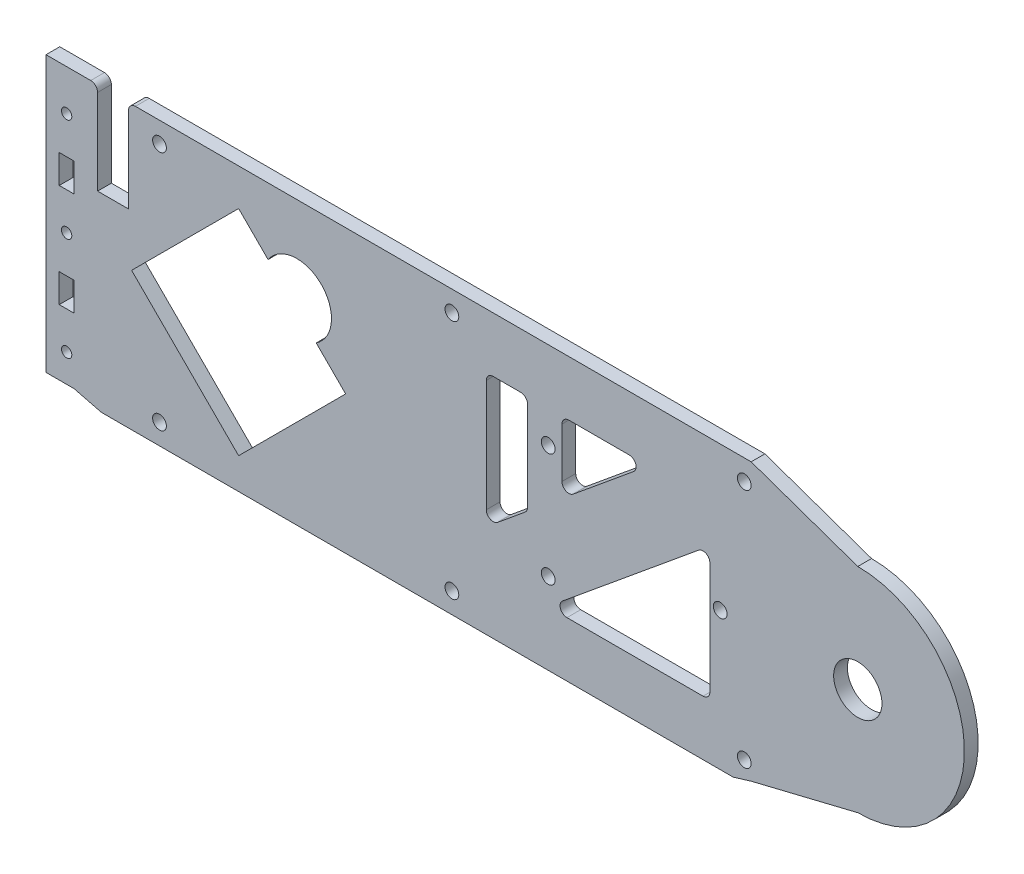
SolidWorks part; units mm, degrees
ref_plane "前视基准面" through (0, 0, 0) normal (0, 0, 1) x (1, 0, 0)
ref_plane "上视基准面" through (0, 0, 0) normal (0, 1, 0) x (1, 0, 0)
ref_plane "右视基准面" through (0, 0, 0) normal (1, 0, 0) x (0, 0, -1)
sketch "草图1" plane through (0, 0, 0) normal (0, 0, 1) x (1, 0, 0)
  line L0 (0.5429, 31.3543) -> (0.5429, 28.3543)
  line L1 (0.5429, 18.8543) -> (0.5429, 10.8543) construction
  line L2 (-1.6071, 10.7043) -> (2.6929, 10.7043)
  line L3 (-1.6071, 10.7043) -> (-1.6071, 19.0043)
  line L4 (-1.6071, 19.0043) -> (2.6929, 19.0043)
  line L5 (2.6929, 10.7043) -> (2.6929, 19.0043)
  line L6 (-1.6071, 10.7043) -> (2.6929, 19.0043) construction
  line L7 (-1.6071, 19.0043) -> (2.6929, 10.7043) construction
  line L8 (2.6929, -19.2957) -> (2.6929, -10.9957)
  line L9 (-1.6071, -19.2957) -> (2.6929, -19.2957)
  line L10 (-1.6071, -19.2957) -> (-1.6071, -10.9957)
  line L11 (-1.6071, -10.9957) -> (2.6929, -10.9957)
  line L12 (0.5429, -0.1457) -> (-6.4571, -0.1457) construction
  line L18 (50.5429, -0.1457) -> (96.7433, -0.1457) construction
  line L19 (50.5429, -0.1457) -> (230.5429, -0.1457) construction
  line L20 (199.5429, -0.1457) -> (199.5429, 38.0043) construction
  line L42 (230.5429, -31.1457) -> (199.5561, -38.7059)
  line L43 (199.5561, -38.7059) -> (174.5429, -46.2957)
  line L44 (174.5429, -46.2957) -> (34.5429, -46.2957)
  line L45 (34.5429, -46.2957) -> (2.6929, -38.2957)
  line L47 (2.6929, -38.2957) -> (-5.4571, -38.2957)
  line L48 (-5.4571, -38.2957) -> (-5.4571, 41.7043)
  line L49 (-5.4571, 41.7043) -> (9.5429, 41.7043)
  line L54 (199.5429, 41.7043) -> (230.5429, 30.8543)
  line L55 (9.5429, 41.7043) -> (9.5429, 14.8543)
  line L57 (9.5429, 14.8543) -> (18.5429, 14.8543)
  line L59 (-5.4571, 41.7043) -> (261.5429, 41.7043) construction
  line L60 (18.5429, 41.7043) -> (199.5429, 41.7043)
  line L61 (18.5429, 41.7043) -> (18.5429, 14.8543)
  circle A0 centre (0.5429, 29.8543) radius 1.5
  circle A1 centre (0.5429, -0.1457) radius 1.5
  circle A2 centre (0.5429, -30.1457) radius 1.5
  circle A15 centre (230.5429, -0.1457) radius 7.02
  circle A16 centre (230.5429, -0.1457) radius 31 construction
  arc A17 (230.5429, -31.1457) -> (230.5429, 30.8543) centre (230.5429, -0.1457) ccw
  point P6 (0.5429, 14.8543)
  dimension "D10" = 3
  dimension "D13" = 14.04
  dimension "D1" = 8.3
  dimension "D2" = 4.3
  dimension "D5" = 50
  dimension "D7" = 15
  dimension "D8" = 60
  dimension "D9" = 30
  dimension "D14" = 180
extrude "凸台-拉伸1" add sketch "草图1" along normal blind 4
sketch "草图2" plane through (0, 0, 4) normal (0, 0, 1) x (1, 0, 0)
  line L7 (50.5429, 13.8543) -> (59.0992, 22.4106) construction
  line L15 (64.5429, -0.1457) -> (73.0992, 8.4106) construction
  line L17 (59.0992, 22.4106) -> (50.5429, 30.967)
  line L19 (19.4302, -0.1457) -> (50.5429, 30.967)
  line L20 (19.4302, -0.1457) -> (50.5429, -31.2584)
  line L21 (50.5429, -31.2584) -> (81.6556, -0.1457)
  line L22 (50.5429, 30.967) -> (81.6556, -0.1457) construction
  line L23 (19.4302, -0.1457) -> (81.6556, -0.1457) construction
  line L24 (50.5429, -31.2584) -> (50.5429, 30.967) construction
  line L25 (73.0992, 8.4106) -> (81.6556, -0.1457)
  circle A0 centre (50.5429, -0.1457) radius 34 construction
  arc A1 (59.0992, 22.4106) -> (73.0992, 8.4106) centre (67.4545, 16.7659) cw
  point P0 (50.5429, -0.1457)
  dimension "D1" = 44
  dimension "D2" = 44
extrude "切除-拉伸1" cut sketch "草图2" against normal blind 4
sketch "草图3" plane through (0, 0, 4) normal (0, 0, 1) x (1, 0, 0)
  line L0 (18.5429, 41.7043) -> (199.5429, 41.7043) construction
  line L1 (18.5429, 41.7043) -> (18.5429, 14.8543) construction
  line L3 (112.5429, -34.2957) -> (197.5429, 35.7043) construction
  line L4 (197.5429, 35.7043) -> (197.5429, -34.2957) construction
  line L5 (197.5429, -34.2957) -> (112.5429, -34.2957) construction
  line L6 (187.5429, -24.2957) -> (140.4162, -24.2957)
  line L7 (140.4162, -24.2957) -> (187.5429, 14.5145)
  line L8 (187.5429, 14.5145) -> (187.5429, -24.2957)
  line L9 (112.5429, -34.2957) -> (112.5429, 35.7043) construction
  line L10 (112.5429, 35.7043) -> (197.5429, 35.7043) construction
  line L11 (122.5429, 25.7043) -> (169.6695, 25.7043)
  line L12 (122.5429, -13.1059) -> (169.6695, 25.7043)
  line L13 (122.5429, -13.1059) -> (122.5429, 25.7043)
  line L14 (50.5429, 30.967) -> (112.5429, 35.7043) construction
  line L15 (81.6556, -0.1457) -> (112.5429, -34.2957) construction
  circle A0 centre (27.5429, 35.7043) radius 2
  circle A1 centre (112.5429, 35.7043) radius 2
  circle A2 centre (197.5429, 35.7043) radius 2
  circle A3 centre (112.5429, -34.2957) radius 2
  circle A4 centre (197.5429, -34.2957) radius 2
  circle A5 centre (27.5429, -34.2957) radius 2
  dimension "D1" = 6
  dimension "D2" = 9
  dimension "D5" = 10
  dimension "D6" = 10
  dimension "D3" = 3
  dimension "D4" = 2
extrude "切除-拉伸2" cut sketch "草图3" against normal blind 4
sketch "草图4" plane through (0, 0, 4) normal (0, 0, 1) x (1, 0, 0)
  line L0 (169.6695, 25.7043) -> (122.5429, 25.7043) construction
  line L1 (134.5429, -7.8425) -> (144.5429, -7.8425)
  line L2 (134.5429, -7.8425) -> (134.5429, 39.251)
  line L3 (134.5429, 39.251) -> (144.5429, 39.251)
  line L4 (144.5429, -7.8425) -> (144.5429, 39.251)
  line L5 (134.5429, -7.8425) -> (144.5429, 39.251) construction
  line L6 (134.5429, 39.251) -> (144.5429, -7.8425) construction
  point P0 (139.5429, 15.7043)
  dimension "D1" = 17
  dimension "D2" = 10
  dimension "D3" = 10
extrude "凸台-拉伸2" add sketch "草图4" against normal blind 4
sketch "草图7" plane through (0, 0, 4) normal (0, 0, 1) x (1, 0, 0)
  line L0 (10.6554, -40.2957) -> (194.3167, -40.2957)
  line L4 (34.5429, -46.2957) -> (2.6929, -38.2957) construction
  line L5 (199.5561, -38.7059) -> (174.5429, -46.2957) construction
  line L7 (10.6554, -40.2957) -> (10.6554, -65.8741)
  line L8 (10.6554, -65.8741) -> (206.1971, -67.6189)
  line L9 (206.1971, -67.6189) -> (194.3167, -40.2957)
  circle A0 centre (190.5429, -0.1457) radius 2
  circle A1 centre (140.5429, 16.3543) radius 2
  circle A2 centre (140.5429, -16.6457) radius 2
  point P12 (27.5429, -34.2957)
  point P25 (230.5429, -0.1457)
  dimension "D1" = 4
  dimension "D2" = 6
  dimension "D4" = 33
extrude "切除-拉伸3" cut sketch "草图7" against normal blind 4
fillet "圆角1" radius 2 12 edges at (18.5429, 41.7043, 2) (9.5429, 41.7043, 2) (187.5429, 14.5145, 2) (187.5429, -24.2957, 2) (140.4162, -24.2957, 2) (144.5429, 5.0118, 2) (144.5429, 25.7043, 2) (169.6695, 25.7043, 2) (134.5429, -3.2235, 2) (122.5429, -13.1059, 2) (134.5429, 25.7043, 2) (122.5429, 25.7043, 2)
